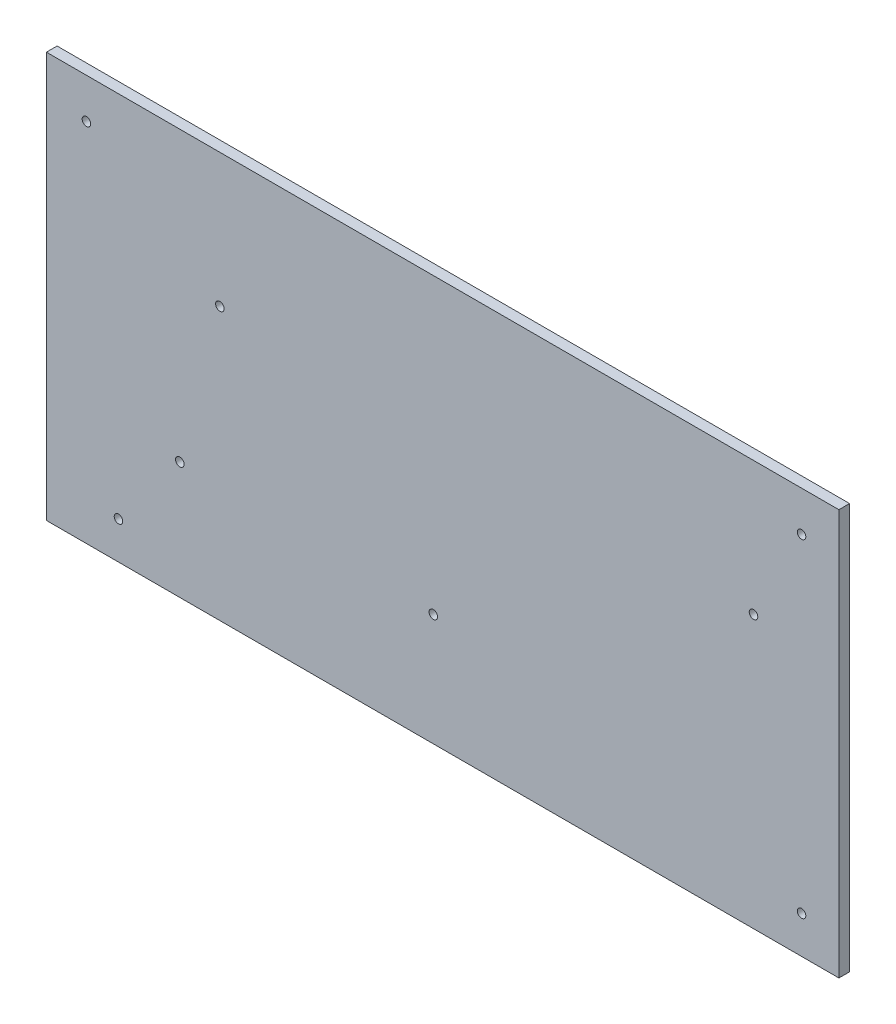
SolidWorks part; units mm, degrees
ref_plane "前视基准面" through (0, 0, 0) normal (0, 0, 1) x (1, 0, 0)
ref_plane "上视基准面" through (0, 0, 0) normal (0, 1, 0) x (1, 0, 0)
ref_plane "右视基准面" through (0, 0, 0) normal (1, 0, 0) x (0, 0, -1)
other "Configuration Table"
sketch "草图1" plane through (0, 0, 0) normal (0, 0, 1) x (1, 0, 0)
  line L1 (-145, -42) -> (152, -42)
  line L2 (-145, -42) -> (-145, 110)
  line L3 (-145, 110) -> (152, 110)
  line L4 (152, -42) -> (152, 110)
  line L5 (-145, -42) -> (152, 110) construction
  line L6 (-145, 110) -> (152, -42) construction
  circle A0 centre (0, 0) radius 1.6
  circle A1 centre (-80, 60) radius 1.6
  circle A2 centre (120, 60) radius 1.6
  circle A3 centre (-95, 2) radius 1.6
  circle A4 centre (-118, -28) radius 1.6
  circle A5 centre (138, -28) radius 1.6
  circle A6 centre (-130, 95) radius 1.6
  circle A7 centre (138, 95) radius 1.6
extrude "凸台-拉伸1" add sketch "草图1" along normal mid plane 4
